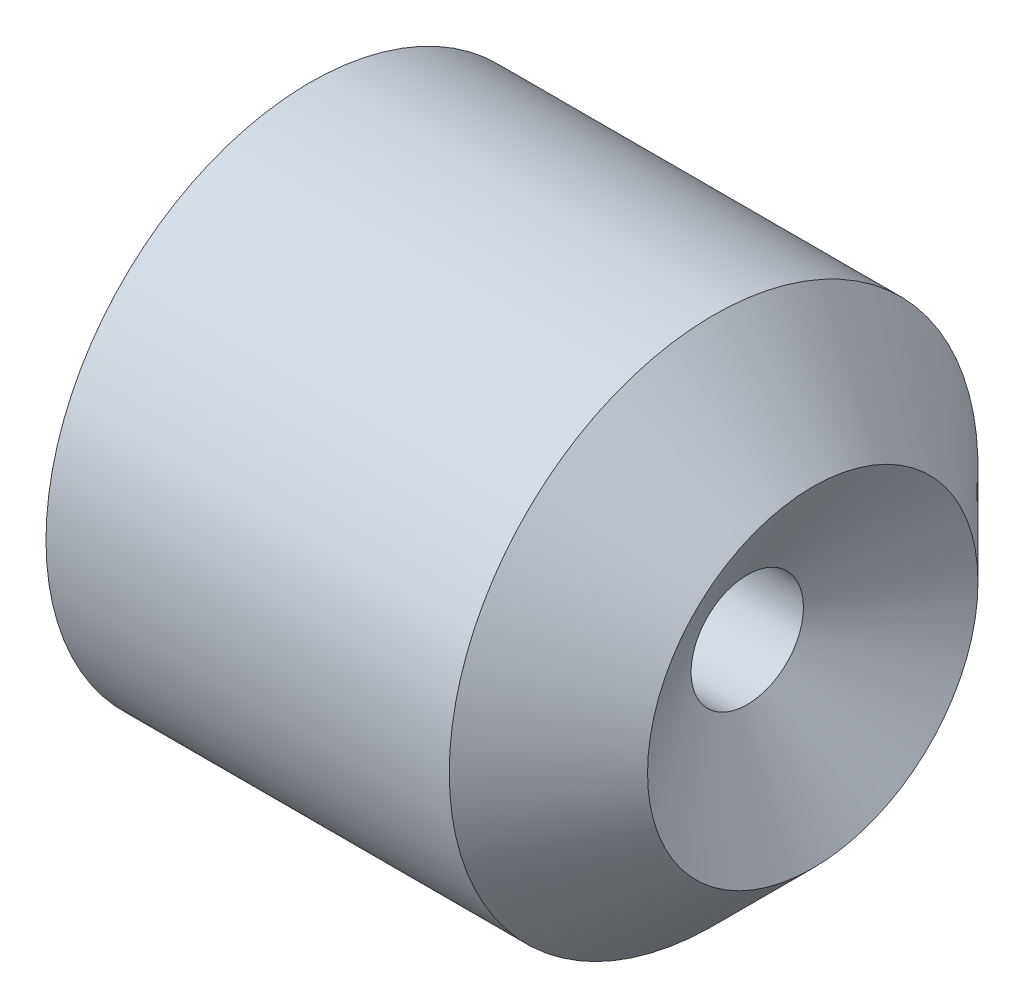
SolidWorks part; units mm, degrees
material "ASTM A574M"
ref_plane "Plane1" through (0, 0, 0) normal (0, 0, 1) x (1, 0, 0)
ref_plane "Plane2" through (0, 0, 0) normal (0, 1, 0) x (1, 0, 0)
ref_plane "Plane3" through (0, 0, 0) normal (1, 0, 0) x (0, 0, -1)
sketch "BodySke" plane through (0, 0, 0) normal (0, 0, 1) x (1, 0, 0)
  line L0 (0, 0) -> (0, 3.3095)
  line L1 (0, 3.3095) -> (0.3987, 4)
  line L2 (0.3987, 4) -> (6.5, 4)
  line L3 (6.5, 4) -> (8, 2.5)
  line L4 (6.4978, 0) -> (0, 0)
  line L5 (-12.7, 0) -> (88.9, 0) construction
  line L6 (6.4978, 0) -> (8, 2.5)
  line L7 (8, 2.5) -> (8, 12.025) construction
  line L8 (0, -3.3095) -> (0.3987, -4) construction
  line L9 (6.4978, 0) -> (8, -2.5) construction
  line L10 (6.5, -4) -> (8, -2.5) construction
  line L11 (1.25, 15.875) -> (1.25, -3.175) construction
  dimension "Length" = 8
  dimension "Diameter" = 8
  dimension "Drive_ch_ang" = 60
  dimension "Minor_dia" = 6.619
  dimension "Cup_nose_ang" = 45
  dimension "Cup_ang" = 118
  dimension "Cup_dia" = 5
  dimension "Advance" = 1.25
revolve "BaseBody" add sketch "BodySke" angle 360 about L5
cosmetic thread "ThreadCosmetic" [suppressed] parameters "Thread_minor"=6.619
cosmetic thread "Cosmetic Thread1" parameters "D2"=6.8
sketch "Sketch2" plane through (0, 0, 0) normal (-1, 0, 0) x (0, 0, 1)
  line L0 (1.1547, 2) -> (-1.1547, 2)
  line L1 (-1.1547, 2) -> (-2.3094, 0)
  line L2 (1.1547, 2) -> (2.3094, 0)
  line L3 (1.1547, -2) -> (2.3094, 0)
  line L4 (1.1547, -2) -> (-1.1547, -2)
  line L5 (-1.1547, -2) -> (-2.3094, 0)
  dimension "Hex_size" = 4
  dimension "D2" = 2
  dimension "D3" = 2
extrude "Hex" cut sketch "Sketch2" against normal blind 4
sketch "Sketch6" plane through (0, 0, 0) normal (-1, 0, 0) x (0, 0, 1)
  circle A0 centre (0, 0) radius 0.85
  dimension "D1" = 1.7
extrude "Cut-Extrude1" cut sketch "Sketch6" against normal through all
